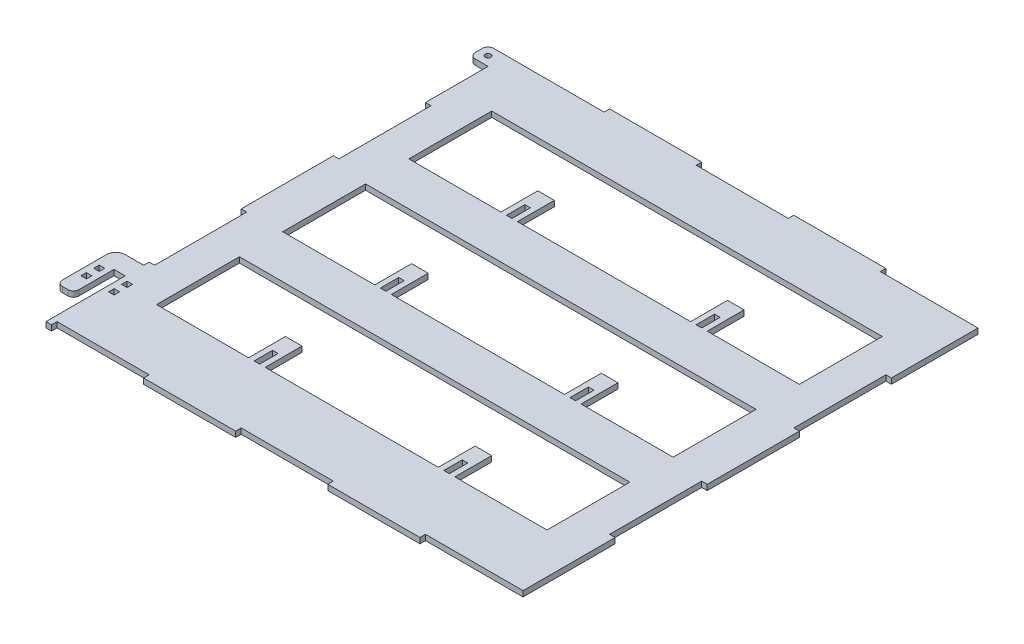
SolidWorks part; units mm, degrees
ref_plane "Front Plane" through (0, 0, 0) normal (0, 0, 1) x (1, 0, 0)
ref_plane "Top Plane" through (0, 0, 0) normal (0, 1, 0) x (1, 0, 0)
ref_plane "Right Plane" through (0, 0, 0) normal (1, 0, 0) x (0, 0, -1)
sketch "Sketch1" plane through (0, 0, 0) normal (0, 1, 0) x (1, 0, 0)
  line L0 (256, 100) -> (256, 150)
  line L1 (3, 0) -> (53, 0)
  line L2 (0, 0) -> (0, 40)
  line L3 (53, 250) -> (103, 250)
  line L4 (256, 0) -> (256, 50)
  line L5 (0, 203) -> (0, 237)
  line L6 (203, 250) -> (153, 250)
  line L7 (0, 50) -> (-10.1, 50)
  line L8 (0, 0) -> (0, -3)
  line L9 (256, 200) -> (253, 200)
  line L10 (0, -3) -> (3, -3)
  line L11 (256, 150) -> (253, 150)
  line L12 (253, 200) -> (253, 150)
  line L13 (203, 0) -> (256, 0)
  line L14 (153, 0) -> (153, -3)
  line L15 (153, -3) -> (203, -3)
  line L16 (203, 0) -> (203, -3)
  line L17 (0, 203) -> (3, 203)
  line L18 (0, 103) -> (0, 153)
  line L19 (0, 153) -> (3, 153)
  line L20 (3, 203) -> (3, 153)
  line L21 (3, 0) -> (3, -3)
  line L22 (103, 0) -> (103, -3)
  line L23 (103, -3) -> (53, -3)
  line L24 (53, 0) -> (53, -3)
  line L25 (-12.1, 28) -> (-9.1, 28)
  line L26 (0, 40) -> (-6.1, 40)
  line L27 (-15.1, 45) -> (-15.1, 43)
  line L28 (-12.1, 28) -> (-12.1, 31)
  line L29 (256, 100) -> (253, 100)
  line L30 (256, 200) -> (256, 247)
  line L31 (256, 50) -> (253, 50)
  line L32 (253, 100) -> (253, 50)
  line L33 (0, 103) -> (3, 103)
  line L34 (103, 0) -> (153, 0)
  line L35 (-7, 247) -> (53, 247)
  line L36 (3, 103) -> (3, 53)
  line L37 (184, 172) -> (234, 172)
  line L38 (-15.1, 43) -> (-15.1, 21)
  line L39 (0, 237) -> (-7, 237)
  line L40 (-10, 244) -> (-10, 240)
  line L41 (-12.1, 18) -> (-9.1, 18)
  line L42 (-6.1, 40) -> (-6.1, 21)
  line L43 (-12.1, 31) -> (-9.1, 31)
  line L44 (-9.1, 28) -> (-9.1, 31)
  line L45 (-12.1, 35) -> (-9.1, 35)
  line L46 (-12.1, 35) -> (-12.1, 38)
  line L47 (-12.1, 38) -> (-9.1, 38)
  line L48 (-9.1, 35) -> (-9.1, 38)
  line L49 (3, 28) -> (6, 28)
  line L50 (3, 28) -> (3, 31)
  line L51 (3, 31) -> (6, 31)
  line L52 (6, 28) -> (6, 31)
  line L53 (3, 35) -> (6, 35)
  line L54 (3, 35) -> (3, 38)
  line L55 (3, 38) -> (6, 38)
  line L56 (6, 35) -> (6, 38)
  line L57 (75, 35) -> (78, 35)
  line L58 (75, 35) -> (75, 45)
  line L59 (203, 250) -> (203, 247)
  line L60 (203, 247) -> (256, 247)
  line L61 (0, 50) -> (0, 53)
  line L62 (103, 250) -> (103, 247)
  line L63 (103, 247) -> (153, 247)
  line L64 (153, 250) -> (153, 247)
  line L65 (0, 53) -> (3, 53)
  line L66 (75, 45) -> (78, 45)
  line L67 (78, 35) -> (78, 45)
  line L68 (53, 250) -> (53, 247)
  line L69 (178, 35) -> (181, 35)
  line L70 (178, 35) -> (178, 45)
  line L71 (178, 45) -> (181, 45)
  line L72 (181, 35) -> (181, 45)
  line L73 (75, 103.5) -> (78, 103.5)
  line L74 (75, 103.5) -> (75, 113.5)
  line L75 (75, 113.5) -> (78, 113.5)
  line L76 (78, 103.5) -> (78, 113.5)
  line L77 (22, 172) -> (72, 172)
  line L78 (178, 103.5) -> (178, 113.5)
  line L79 (178, 113.5) -> (181, 113.5)
  line L80 (181, 103.5) -> (181, 113.5)
  line L82 (75, 172) -> (75, 182)
  line L83 (75, 182) -> (78, 182)
  line L84 (78, 172) -> (78, 182)
  line L86 (178, 172) -> (178, 182)
  line L87 (178, 182) -> (181, 182)
  line L88 (181, 172) -> (181, 182)
  line L89 (22, 35) -> (72, 35)
  line L90 (22, 35) -> (22, 80)
  line L91 (22, 80) -> (234, 80)
  line L92 (234, 35) -> (234, 80)
  line L93 (22, 103.5) -> (72, 103.5)
  line L94 (72, 35) -> (72, 55)
  line L95 (72, 55) -> (81, 55)
  line L96 (81, 35) -> (81, 55)
  line L97 (22, 103.5) -> (22, 148.5)
  line L98 (175, 35) -> (175, 55)
  line L99 (175, 55) -> (184, 55)
  line L100 (184, 35) -> (184, 55)
  line L101 (81, 35) -> (175, 35)
  line L102 (22, 148.5) -> (234, 148.5)
  line L103 (184, 35) -> (234, 35)
  line L104 (234, 103.5) -> (234, 148.5)
  line L105 (22, 172) -> (22, 217)
  line L106 (72, 103.5) -> (72, 123.5)
  line L107 (72, 123.5) -> (81, 123.5)
  line L108 (81, 103.5) -> (81, 123.5)
  line L109 (22, 217) -> (234, 217)
  line L110 (175, 103.5) -> (175, 123.5)
  line L111 (175, 123.5) -> (184, 123.5)
  line L112 (184, 103.5) -> (184, 123.5)
  line L113 (81, 103.5) -> (175, 103.5)
  line L114 (178, 103.5) -> (181, 103.5)
  line L115 (184, 103.5) -> (234, 103.5)
  line L116 (234, 172) -> (234, 217)
  line L117 (75, 172) -> (78, 172)
  line L118 (72, 172) -> (72, 192)
  line L119 (72, 192) -> (81, 192)
  line L120 (81, 172) -> (81, 192)
  line L121 (178, 172) -> (181, 172)
  line L122 (175, 172) -> (175, 192)
  line L123 (175, 192) -> (184, 192)
  line L124 (184, 172) -> (184, 192)
  line L125 (81, 172) -> (175, 172)
  circle A0 centre (-5, 242) radius 1.5
  arc A1 (-7, 247) -> (-10, 244) centre (-7, 244) ccw
  arc A2 (-7, 237) -> (-10, 240) centre (-7, 240) cw
  arc A3 (-10.1, 50) -> (-15.1, 45) centre (-10.1, 45) ccw
  arc A4 (-9.1, 18) -> (-6.1, 21) centre (-9.1, 21) ccw
  arc A5 (-15.1, 21) -> (-12.1, 18) centre (-12.1, 21) ccw
  point P45 (-10, 247)
  point P48 (-10, 237)
  point P67 (-15.1, 50)
  point P70 (-6.1, 18)
  point P73 (-15.1, 18)
  dimension "D7" = 5
  dimension "D8" = 3
  dimension "D9" = 5
  dimension "D10" = 3
  dimension "D45" = 5
  dimension "D46" = 3
  dimension "D12" = 3
  dimension "D84" = 3
  dimension "D1" = 256
  dimension "D3" = 50
  dimension "D4" = 3
  dimension "D5" = 10
  dimension "D6" = 10
  dimension "D11" = 34
  dimension "D13" = 53
  dimension "D14" = 3
  dimension "D15" = 3
  dimension "D16" = 50
  dimension "D17" = 50
  dimension "D18" = 50
  dimension "D19" = 53
  dimension "D20" = 3
  dimension "D21" = 3
  dimension "D22" = 50
  dimension "D23" = 50
  dimension "D24" = 50
  dimension "D25" = 50
  dimension "D26" = 50
  dimension "D27" = 3
  dimension "D28" = 3
  dimension "D29" = 50
  dimension "D30" = 50
  dimension "D31" = 9
  dimension "D32" = 15.1
  dimension "D33" = 25
  dimension "D34" = 7
  dimension "D35" = 40
  dimension "D36" = 4
  dimension "D37" = 4
  dimension "D38" = 10
  dimension "D39" = 3
  dimension "D40" = 10
  dimension "D41" = 3
  dimension "D42" = 3
  dimension "D43" = 3
  dimension "D44" = 3
  dimension "D47" = 6.1
  dimension "D48" = 50
  dimension "D49" = 50
  dimension "D50" = 50
  dimension "D51" = 53
  dimension "D52" = 247
  dimension "D53" = 47
  dimension "D54" = 3
  dimension "D55" = 50
  dimension "D56" = 3
  dimension "D57" = 10
  dimension "D58" = 10
  dimension "D59" = 20
  dimension "D60" = 10
  dimension "D61" = 100
  dimension "D62" = 3
  dimension "D63" = 75
  dimension "D64" = 3
  dimension "D65" = 65
  dimension "D66" = 10
  dimension "D67" = 3
  dimension "D68" = 3
  dimension "D69" = 65
  dimension "D70" = 10
  dimension "D71" = 10
  dimension "D72" = 3
  dimension "D73" = 45
  dimension "D74" = 45
  dimension "D75" = 3
  dimension "D76" = 3
  dimension "D77" = 3
  dimension "D78" = 50
  dimension "D79" = 50
  dimension "D80" = 20
  dimension "D81" = 20
  dimension "D82" = 90
  dimension "D83" = 90
  dimension "D85" = 3
  dimension "D86" = 3
  dimension "D87" = 5
  dimension "D88" = 5
  dimension "D89" = 90
  dimension "D90" = 100
  dimension "D91" = 75
  dimension "D92" = 3
  dimension "D93" = 20
  dimension "D94" = 3
  dimension "D95" = 45
  dimension "D96" = 45
  dimension "D97" = 20
  dimension "D98" = 10
  dimension "D99" = 3
  dimension "D100" = 20
  dimension "D101" = 20
  dimension "D102" = 3
  dimension "D103" = 3
  dimension "D104" = 58.5
  dimension "D105" = 75
  dimension "D106" = 50
  dimension "D107" = 50
  dimension "D108" = 100
  dimension "D109" = 10
  dimension "D110" = 90
  dimension "D111" = 3
  dimension "D112" = 3
  dimension "D113" = 10
  dimension "D114" = 20
  dimension "D115" = 3
  dimension "D116" = 3
  dimension "D117" = 10
  dimension "D118" = 20
  dimension "D119" = 45
  dimension "D120" = 50
  dimension "D121" = 50
  dimension "D122" = 58.5
extrude "Boss-Extrude1" add sketch "Sketch1" along normal blind 3
equation "\"w\"=3"
equation "\"L\"=50"
